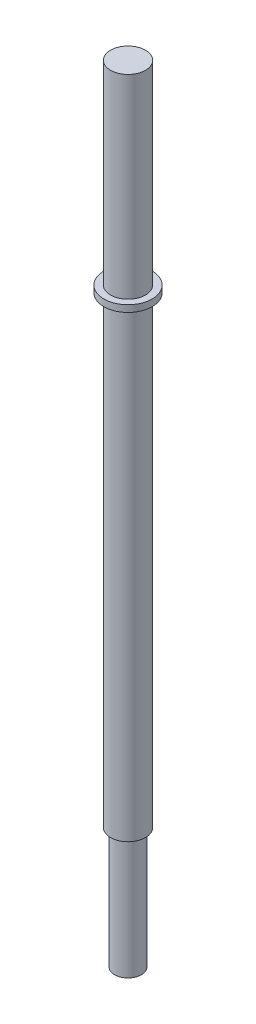
SolidWorks part; units mm, degrees
ref_plane "Front Plane" through (0, 0, 0) normal (0, 0, 1) x (1, 0, 0)
ref_plane "Top Plane" through (0, 0, 0) normal (0, 1, 0) x (1, 0, 0)
ref_plane "Right Plane" through (0, 0, 0) normal (1, 0, 0) x (0, 0, -1)
sketch "Sketch1" plane through (0, 0, 0) normal (0, 0, 1) x (1, 0, 0)
  line L0 (0, 0) -> (0.6604, 0)
  line L1 (0.6604, 0) -> (0.6604, -25.146)
  line L2 (0.6604, -25.146) -> (0.508, -25.146)
  line L3 (0.508, -25.146) -> (0.508, -29.718)
  line L4 (0.508, -29.718) -> (0, -29.718)
  line L5 (0, -29.718) -> (0, 0)
  line L6 (0.6604, -7.366) -> (0.9144, -7.366)
  line L7 (0.9144, -7.366) -> (0.9144, -7.62)
  line L8 (0.9144, -7.62) -> (0.6604, -7.62)
  line L9 (0, 0) -> (0, 14.3765) construction
  dimension "D1" = 0.6604
  dimension "D2" = 29.718
  dimension "D3" = 25.146
  dimension "D4" = 0.508
  dimension "D5" = 7.62
  dimension "D6" = 0.254
revolve "Revolve2" add sketch "Sketch1" angle 360 about L9
